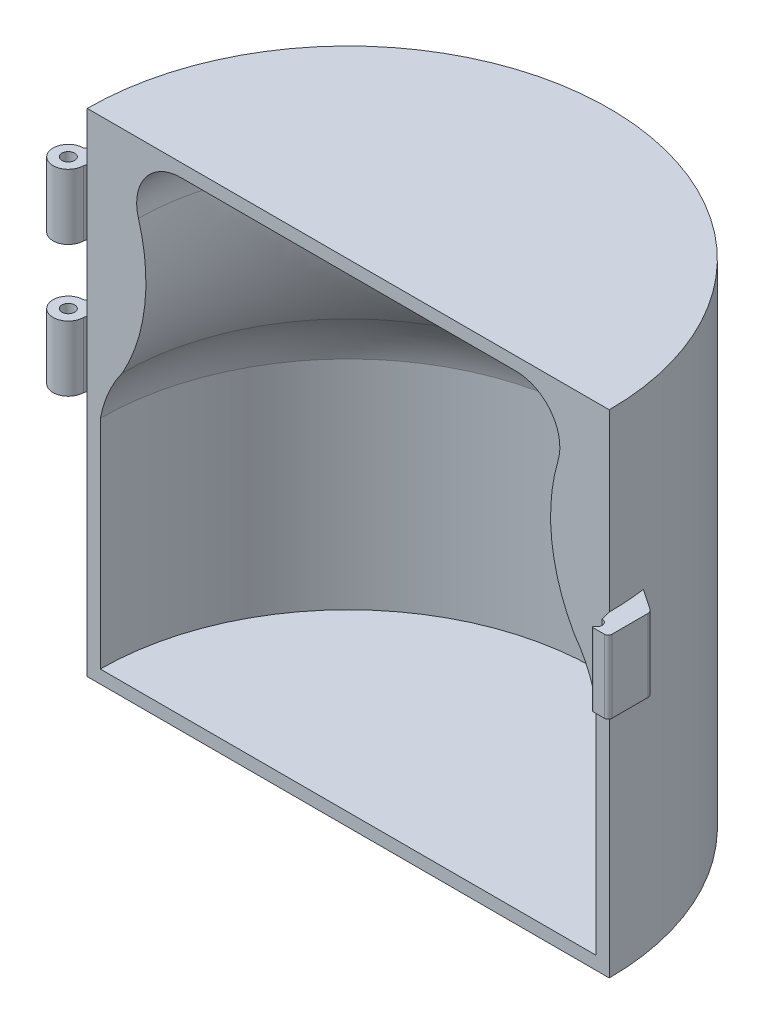
SolidWorks part; units mm, degrees
ref_plane "Front Plane" through (0, 0, 0) normal (0, 0, 1) x (1, 0, 0)
ref_plane "Top Plane" through (0, 0, 0) normal (0, 1, 0) x (1, 0, 0)
ref_plane "Right Plane" through (0, 0, 0) normal (1, 0, 0) x (0, 0, -1)
sketch "Sketch1" plane through (0, 0, 0) normal (0, 0, 1) x (1, 0, 0)
  line L0 (0, 27.2592) -> (23.0119, 27.2592)
  line L1 (0, 27.2092) -> (23.0119, 27.2092) construction
  line L2 (0, -36.677) -> (34, -36.677) construction
  line L3 (34, -36.677) -> (34, -6.9013) construction
  line L9 (34.05, -36.727) -> (34.05, -6.8965)
  line L10 (0, -36.727) -> (34.05, -36.727)
  line L11 (0, 27.2592) -> (0, 29.0592)
  line L12 (0, 0) -> (0, 40) construction
  line L13 (0, 29.0592) -> (35.85, 29.0592)
  line L14 (35.85, 29.0592) -> (35.85, -38.527)
  line L15 (35.85, -38.527) -> (0, -38.527)
  line L16 (0, 0) -> (0, -45) construction
  line L17 (0, -38.527) -> (0, -36.727)
  line L18 (0, 0) -> (0, 43) construction
  arc A0 (30.9693, 0) -> (34, -6.9013) centre (17.1484, -10.1856) cw construction
  arc A1 (30.9693, 0) -> (28.7683, 19.5169) centre (53.0642, 12.3743) cw construction
  arc A2 (28.7683, 19.5169) -> (23.0119, 27.2092) centre (23.0119, 21.2092) ccw construction
  arc A3 (28.8162, 19.5028) -> (23.0119, 27.2592) centre (23.0119, 21.2092) ccw
  arc A4 (31.0114, 0.0271) -> (28.8162, 19.5028) centre (53.0642, 12.3743) cw
  arc A5 (31.0114, 0.0271) -> (34.05, -6.8965) centre (17.1484, -10.1856) cw
  dimension "D2" = 1.8
  dimension "D3" = 1.8
  dimension "D4" = 1.8
  dimension "D1" = 0.05
revolve "Revolve1" add sketch "Sketch1" angle 180 about L18
sketch "Sketch2" plane through (0, 0, 0) normal (0, 0, 1) x (1, 0, 0)
  line L0 (-35.85, 29.0592) -> (-35.85, -38.527) construction
  line L1 (-38.46, 29.0592) -> (-38.46, -10.9408) construction
  line L2 (-35.85, 29.0592) -> (-38.46, 29.0592) construction
  line L3 (-37.6, 20.386) -> (-35.85, 20.386)
  line L4 (-35.85, 20.386) -> (-35.85, 13.0957)
  line L5 (-35.85, 13.0957) -> (-37.6, 13.0957)
  line L6 (-37.6, 13.0957) -> (-37.6, 20.386)
  point P10 (0, 0)
  dimension "D1" = 40
  dimension "D2" = 0.86
  dimension "D3" = 1.75
revolve "Revolve2" [suppressed] add sketch "Sketch2" angle 360 about L1
sketch "Sketch3" plane through (0, 0, 0) normal (0, 1, 0) x (1, 0, 0)
  line L0 (0, 0) -> (-38.45, 0) construction
  line L1 (-35.8354, 1.0218) -> (-35.6652, 1.7243)
  line L2 (-35.6652, 1.7243) -> (-35.5528, 4.6067)
  circle A0 centre (-38.45, 0) radius 0.875
  circle A1 centre (-38.45, 0) radius 2.1 construction
  arc A2 (-35.5528, 4.6067) -> (-38.45, 2.1) centre (-59.4902, 29.3458) cw
  arc A3 (35.85, 0) -> (-35.85, 0) centre (0, 0) ccw construction
  arc A4 (-36.35, 0) -> (-35.8354, 1.0218) centre (-34.0891, -0.4981) cw
  arc A5 (-38.45, 2.1) -> (-36.35, 0) centre (-38.45, 0) ccw
  dimension "D1" = 1.75
  dimension "D3" = 4.2
  dimension "D2" = 2.6
extrude "Boss-Extrude1" add sketch "Sketch3" along normal blind 22 and the other way blind 5
sketch "Sketch4" plane through (0, 0, 0) normal (0, 0, 1) x (1, 0, 0)
  line L0 (-35.8354, 22) -> (-40.55, 22) construction
  line L1 (-35.8354, 22) -> (-35.85, 13.05) construction
  line L2 (-35.85, -38.527) -> (-35.85, 29.0592) construction
  line L3 (-35.85, 13.05) -> (-40.55, 13.05)
  line L4 (-40.55, 22) -> (-40.55, -5) construction
  line L5 (-40.55, 13.05) -> (-40.55, 3.95)
  line L6 (-40.55, 3.95) -> (-35.85, 3.95)
  line L7 (-35.85, 3.95) -> (-35.85, 13.05)
  line L8 (-35.8354, -5) -> (-40.55, -5) construction
  line L9 (0, 0) -> (0, 30.4672) construction
  dimension "D1" = 8.95
  dimension "D2" = 8.95
sketch "Sketch5" plane through (0, 0, 0) normal (0, 1, 0) x (1, 0, 0)
  line L0 (35.8253, -1.33) -> (36.1933, -1.3437) construction
  line L1 (35.7383, -2.8275) -> (36.1371, -2.859) construction
  line L2 (36.1933, -1.3437) -> (36.1371, -2.859) construction
  line L3 (35.85, 0) -> (35.8253, -1.33) construction
  line L4 (36.1946, -1.309) -> (36.1371, -2.859) construction
  line L5 (36.1946, -1.309) -> (35.85, 0)
  line L6 (36.4151, -2.8184) -> (36.4382, -2.8862)
  line L7 (36.5518, -2.9676) -> (37.1694, -2.9676)
  line L8 (37.1694, -2.9676) -> (38.166, -2.9676)
  line L11 (38.666, -2.4676) -> (38.666, 2.4853)
  line L12 (38.3373, 3.1058) -> (35.4945, 5.036)
  circle A0 centre (0, 0) radius 35.85 construction
  arc A1 (36.1933, -1.3437) -> (36.1371, -2.859) centre (36.1652, -2.1013) cw construction
  arc A2 (36.1946, -1.309) -> (36.1371, -2.859) centre (36.1659, -2.084) cw construction
  arc A3 (36.1946, -1.309) -> (36.4151, -2.8184) centre (36.1659, -2.084) cw
  arc A4 (36.4382, -2.8862) -> (36.5518, -2.9676) centre (36.5518, -2.8476) ccw
  arc A6 (35.4945, 5.036) -> (35.85, 0) centre (0, 0) cw
  arc A7 (38.666, -2.4676) -> (38.166, -2.9676) centre (38.166, -2.4676) cw
  arc A8 (38.666, 2.4853) -> (38.3373, 3.1058) centre (37.916, 2.4853) ccw
  point P15 (36.1659, -2.084)
  dimension "D5" = 0.12
  dimension "D6" = 0.5
  dimension "D7" = 0.75
  dimension "D1" = 1.5
  dimension "D2" = 0.4
  dimension "D3" = 1.33
  dimension "D4" = 1.55
extrude "Boss-Extrude2" add sketch "Sketch5" along normal blind 5 and the other way blind 5
revolve "Cut-Revolve1" cut sketch "Sketch4" angle 9 about L9 other way angle 9
